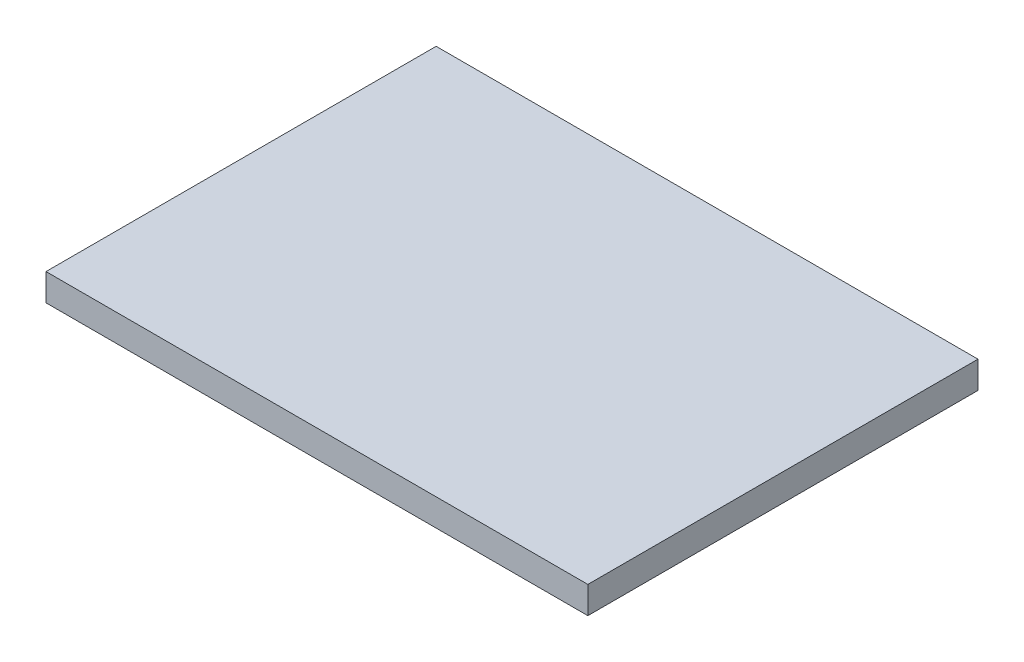
SolidWorks part; units mm, degrees
ref_plane "Front Plane" through (0, 0, 0) normal (0, 0, 1) x (1, 0, 0)
ref_plane "Top Plane" through (0, 0, 0) normal (0, 1, 0) x (1, 0, 0)
ref_plane "Right Plane" through (0, 0, 0) normal (1, 0, 0) x (0, 0, -1)
sketch "Sketch1" plane through (0, 0, 0) normal (0, 1, 0) x (1, 0, 0)
  line L1 (0, 0) -> (63.5, 0)
  line L2 (0, 0) -> (0, 45.72)
  line L3 (0, 45.72) -> (63.5, 45.72)
  line L4 (63.5, 0) -> (63.5, 45.72)
  dimension "D1" = 45.72
  dimension "D2" = 63.5
extrude "Boss-Extrude1" add sketch "Sketch1" along normal blind 3.175
